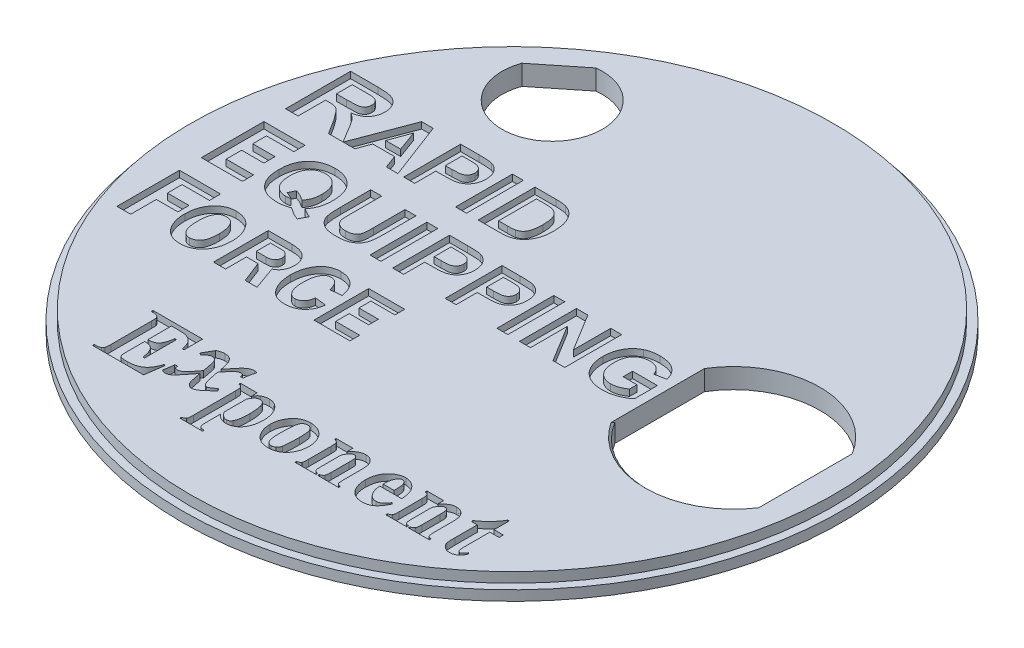
SolidWorks part; units mm, degrees
material "6061 Alloy"
ref_plane "Front Plane" through (0, 0, 0) normal (0, 0, 1) x (1, 0, 0)
ref_plane "Top Plane" through (0, 0, 0) normal (0, 1, 0) x (1, 0, 0)
ref_plane "Right Plane" through (0, 0, 0) normal (1, 0, 0) x (0, 0, -1)
sketch "Sketch1" plane through (0, 0, 0) normal (0, 1, 0) x (1, 0, 0)
  circle A0 centre (0, 0) radius 20.828
  dimension "D1" = 41.656
extrude "Boss-Extrude1" add sketch "Sketch1" along normal blind 1.27
sketch "Sketch2" plane through (0, 1.27, 0) normal (0, 1, 0) x (1, 0, 0)
  circle A0 centre (0, 0) radius 20.32
  circle A1 centre (0, 0) radius 20.828
  circle A2 centre (0, 0) radius 20.828 construction
  dimension "D1" = 0.508
extrude "Cut-Extrude2" cut sketch "Sketch2" against normal blind 0.635
sketch "Sketch3" plane through (0, 1.27, 0) normal (0, 1, 0) x (1, 0, 0)
  line L0 (20.828, 3.7545) -> (20.828, -12.2477) construction
  line L1 (0, 0) -> (20.828, 0) construction
  line L2 (18.6677, 2.8354) -> (18.6677, -2.8354)
  line L3 (9.3332, 2.8354) -> (9.3332, -2.8354)
  arc A0 (9.3332, -2.8354) -> (18.6677, -2.8354) centre (14.0005, 0) ccw
  circle A1 centre (0, 0) radius 20.828 construction
  arc A2 (18.6677, 2.8354) -> (9.3332, 2.8354) centre (14.0005, 0) ccw
  dimension "D1" = 10.922
  dimension "D3" = 4.6672
  dimension "D2" = 14.0005
extrude "Cut-Extrude3" cut sketch "Sketch3" against normal through all
chamfer "Chamfer1" distance 0.127 angle 45 1 edges at (14.0005, 1.27, 5.461)
sketch "Sketch12" plane through (0, 0, 0) normal (0, -1, 0) x (1, 0, 0)
  line L1 (-7.6581, 18.2626) -> (5.6769, 18.2626)
  line L2 (-9.2456, 16.6751) -> (-9.2456, 3.3401)
  line L3 (-7.6581, 1.7526) -> (5.6769, 1.7526)
  line L4 (7.2644, 16.6751) -> (7.2644, 3.3401)
  line L5 (-9.2456, 18.2626) -> (7.2644, 1.7526) construction
  line L6 (-9.2456, 1.7526) -> (7.2644, 18.2626) construction
  arc A0 (-9.2456, 16.6751) -> (-7.6581, 18.2626) centre (-7.6581, 16.6751) cw
  arc A1 (-7.6581, 1.7526) -> (-9.2456, 3.3401) centre (-7.6581, 3.3401) cw
  arc A2 (7.2644, 3.3401) -> (5.6769, 1.7526) centre (5.6769, 3.3401) cw
  arc A3 (7.2644, 16.6751) -> (5.6769, 18.2626) centre (5.6769, 16.6751) ccw
  point P0 (-0.9906, 10.0076)
  dimension "D3" = 16.51
  dimension "D4" = 1.5875
  dimension "D1" = 10.0076
  dimension "D2" = 0.9906
extrude "Cut-Extrude4" cut sketch "Sketch12" against normal blind 0.508
sketch "Sketch13" plane through (0, 0, 0) normal (0, -1, 0) x (1, 0, 0)
  line L0 (-13.1479, -13.7739) -> (-10.5519, -15.8507)
  line L1 (-16.7984, -13.2341) -> (-6.871, -21.176) construction
  line L2 (-13.0111, -16.2639) -> (0, 0) construction
  arc A0 (-10.5519, -15.8507) -> (-13.1479, -13.7739) centre (-10.16, -12.7) ccw
  circle A1 centre (0, 0) radius 20.828 construction
  dimension "D3" = 6.35
  dimension "D4" = 2.7051
  dimension "D1" = 12.7
  dimension "D2" = 10.16
extrude "Cut-Extrude5" cut sketch "Sketch13" against normal through all
sketch "Sketch16" plane through (0, 1.27, 0) normal (0, 1, 0) x (1, 0, 0)
  line L0 (-18.542, 3.81) -> (-18.542, -1.524) construction
  line L1 (-18.542, -1.524) -> (-18.542, -6.858) construction
  text T0 "R" font "Arial" height in points 16
  text T1 "E" font "Franklin Gothic Medium" height in points 16
  text T2 "F" font "Franklin Gothic Medium" height in points 16
  text T3 "APID" font "Arial" height in points 14
  text T4 "QUIPPING" font "Arial" height in points 14
  text T5 "ORCE" font "Franklin Gothic Medium" height in points 14
  text T6 "E  ponent" font "Times New Roman" height in points 16
  text T7 "x" font "Palatino Linotype" height in points 16
  dimension "D1" = 4.064
  dimension "D2" = 5.334
  dimension "D3" = 18.542
  dimension "D4" = 3.81
  dimension "D5" = 3.302
  dimension "D6" = 2.794
  dimension "D7" = 11.43
  dimension "D8" = 15.24
  dimension "D9" = 3.81
  dimension "D10" = 0.889
extrude "Cut-Extrude7" cut sketch "Sketch16" against normal offset from surface (0.4064 mm away) 0.3556 up to face at (-0.9906, 0.508, 10.0076)
